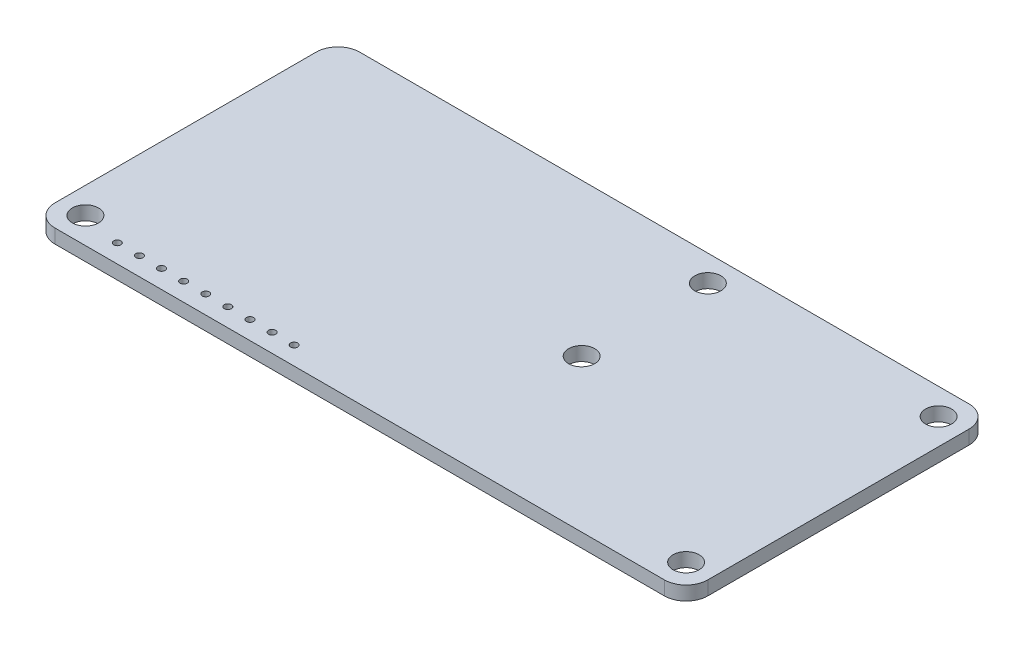
SolidWorks part; units mm, degrees
ref_plane "Front Plane" through (0, 0, 0) normal (0, 0, 1) x (1, 0, 0)
ref_plane "Top Plane" through (0, 0, 0) normal (0, 1, 0) x (1, 0, 0)
ref_plane "Right Plane" through (0, 0, 0) normal (1, 0, 0) x (0, 0, -1)
sketch "Sketch1" plane through (0, 0, 0) normal (0, 1, 0) x (1, 0, 0)
  line L1 (-35, 17.5) -> (35, 17.5)
  line L2 (-37.5, 15) -> (-37.5, -15)
  line L3 (-35, -17.5) -> (35, -17.5)
  line L4 (37.5, 15) -> (37.5, -15)
  line L5 (-37.5, 17.5) -> (37.5, -17.5) construction
  line L6 (-37.5, -17.5) -> (37.5, 17.5) construction
  arc A0 (-37.5, -15) -> (-35, -17.5) centre (-35, -15) ccw
  arc A1 (35, -17.5) -> (37.5, -15) centre (35, -15) ccw
  arc A2 (35, 17.5) -> (37.5, 15) centre (35, 15) cw
  arc A3 (-35, 17.5) -> (-37.5, 15) centre (-35, 15) ccw
  point P0 (0, 0)
  dimension "D3" = 2.5
  dimension "D1" = 75
  dimension "D2" = 35
extrude "Boss-Extrude1" add sketch "Sketch1" along normal blind 1.6
sketch "Sketch2" plane through (0, 1.6, 0) normal (0, 1, 0) x (1, 0, 0)
  line L0 (0, 0) -> (34.5, 0) construction
  line L1 (-34.5, -14.5) -> (34.5, -14.5) construction
  line L2 (-34.5, -14.5) -> (-34.5, 14.5) construction
  line L3 (-34.5, 14.5) -> (34.5, 14.5) construction
  line L4 (34.5, -14.5) -> (34.5, 14.5) construction
  line L5 (-34.5, -14.5) -> (34.5, 14.5) construction
  line L6 (-34.5, 14.5) -> (34.5, -14.5) construction
  line L7 (34.5, 0) -> (8, 14.5) construction
  line L8 (8, 14.5) -> (8, 0) construction
  circle A0 centre (-34.5, -14.5) radius 1.5
  circle A1 centre (34.5, -14.5) radius 1.5
  circle A2 centre (34.5, 14.5) radius 1.5
  circle A3 centre (8, 0) radius 1.5
  circle A4 centre (8, 14.5) radius 1.5
  circle A5 centre (-29.9402, -15.3993) radius 0.4066
  circle A6 centre (-27.4002, -15.3993) radius 0.4066
  circle A7 centre (-24.8602, -15.3993) radius 0.4066
  circle A8 centre (-22.3202, -15.3993) radius 0.4066
  circle A9 centre (-19.7802, -15.3993) radius 0.4066
  circle A10 centre (-17.2402, -15.3993) radius 0.4066
  circle A11 centre (-14.7002, -15.3993) radius 0.4066
  circle A12 centre (-12.1602, -15.3993) radius 0.4066
  circle A13 centre (-9.6202, -15.3993) radius 0.4066
  point P0 (0, 0)
  point P17 (-29.9402, -15.3993)
  dimension "D3" = 3
  dimension "D1" = 69
  dimension "D2" = 29
  dimension "D4" = 26.5
  dimension "D6" = 2.54
  dimension "D5" = 9
extrude "Cut-Extrude1" cut sketch "Sketch2" against normal through all
